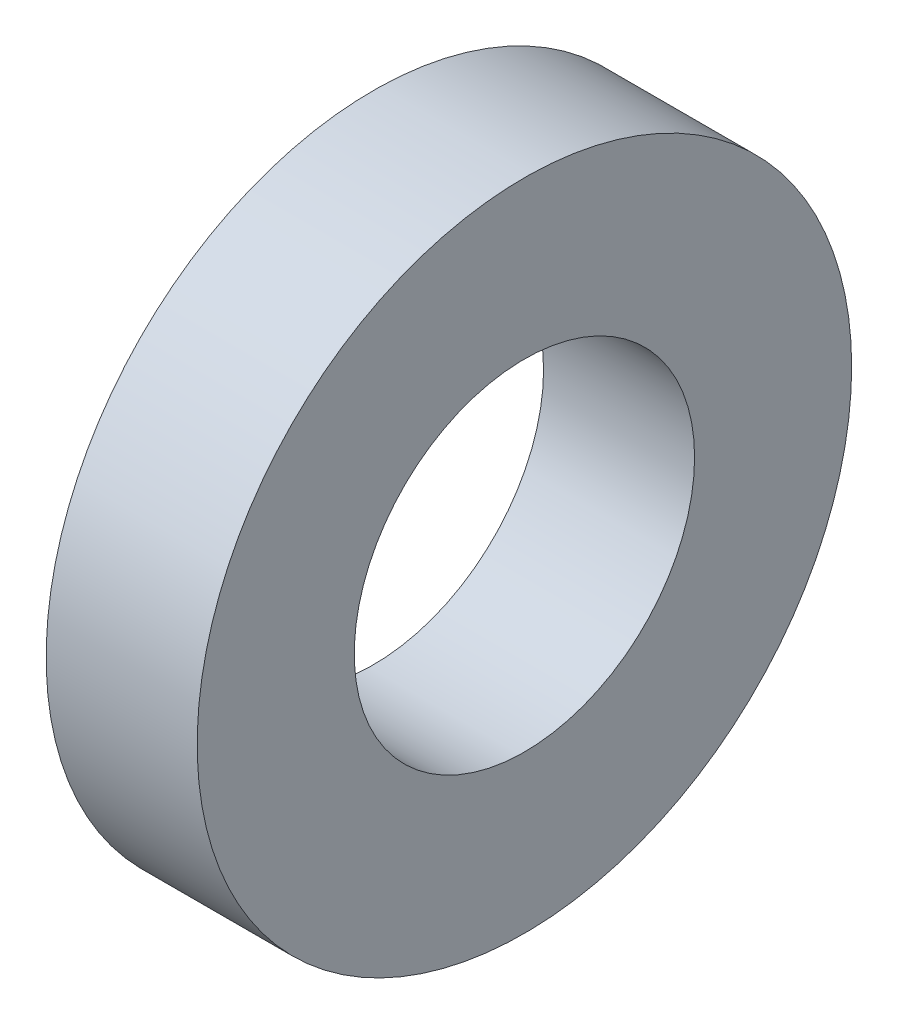
SolidWorks part; units mm, degrees
ref_plane "Front Plane" through (0, 0, 0) normal (0, 0, 1) x (1, 0, 0)
ref_plane "Top Plane" through (0, 0, 0) normal (0, 1, 0) x (1, 0, 0)
ref_plane "Right Plane" through (0, 0, 0) normal (1, 0, 0) x (0, 0, -1)
sketch "Sketch1" plane through (0, 0, 0) normal (1, 0, 0) x (0, 0, -1)
  circle A0 centre (0, 0) radius 32.5
  circle A1 centre (0, 0) radius 16.9
  dimension "D1" = 33.8
  dimension "D2" = 65
extrude "Boss-Extrude1" add sketch "Sketch1" along normal blind 15
